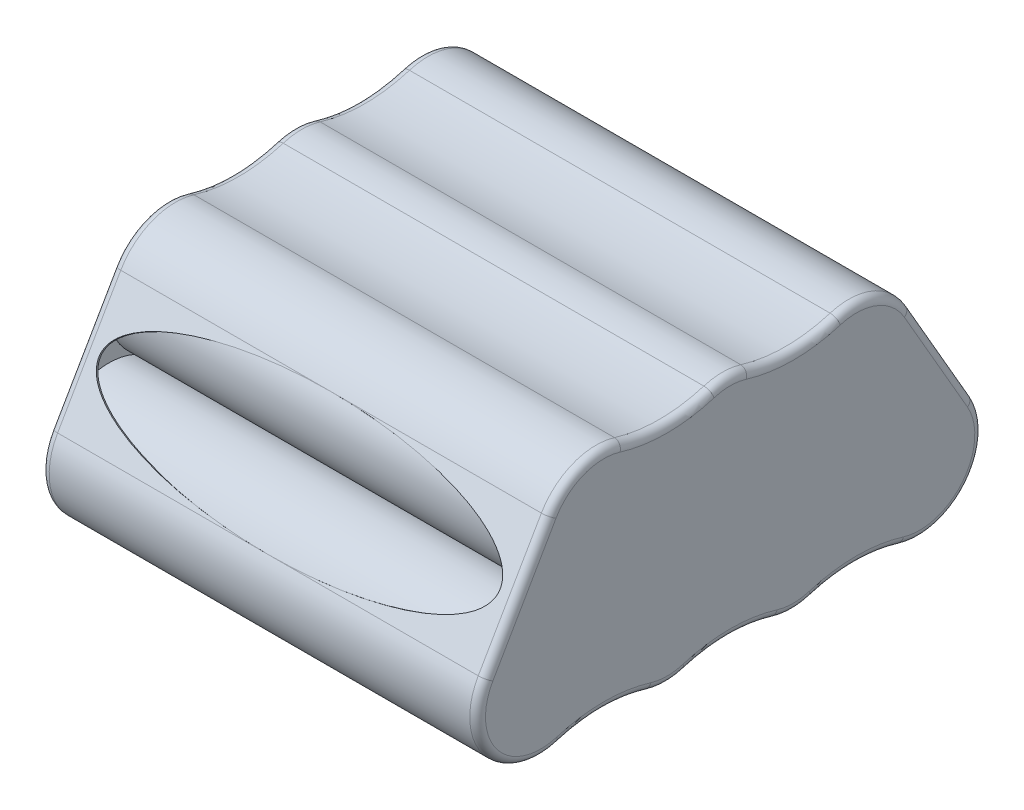
SolidWorks part; units mm, degrees
ref_plane "Front Plane" through (0, 0, 0) normal (0, 0, 1) x (1, 0, 0)
ref_plane "Top Plane" through (0, 0, 0) normal (0, 1, 0) x (1, 0, 0)
ref_plane "Right Plane" through (0, 0, 0) normal (1, 0, 0) x (0, 0, -1)
sketch "Sketch1" plane through (0, 0, 0) normal (1, 0, 0) x (0, 0, -1)
  circle A25 centre (0, 7.2346) radius 7.2346
  circle A26 centre (-14.4693, 7.2346) radius 7.2346
  circle A27 centre (14.4693, 7.2346) radius 7.2346
  circle A28 centre (-7.2346, -5.2961) radius 7.2346
  circle A29 centre (7.2346, -5.2961) radius 7.2346
  circle A30 centre (21.7039, -5.2961) radius 7.2346
  circle A32 centre (-21.7039, -5.2961) radius 7.2346
  circle A33 centre (-7.2346, 30.8876) radius 17.5
  circle A34 centre (7.2346, 30.8876) radius 17.5
  circle A35 centre (38.5706, 12.7957) radius 17.5
  circle A36 centre (14.4693, -28.9491) radius 17.5
  circle A37 centre (0, -28.9491) radius 17.5
  circle A38 centre (-14.4693, -28.9491) radius 17.5
  circle A39 centre (-38.5706, 12.7957) radius 17.5
  point P3 (0, 0)
  point P18 (0, 14.4693)
  point P19 (-7.2346, -12.5307)
  point P36 (0, 0)
  dimension "D1" = 27
  dimension "D2" = 35
extrude "Boss-Extrude2" add sketch "Sketch1" along normal mid plane 50
ref_plane "Plane1" through (0, 11.6913, 20.25) normal (0, 0.5, 0.866) x (1, 0, 0)
sketch "Sketch3" plane through (25, 0, 0) normal (1, 0, 0) x (0, 0, -1)
  line L0 (-20.7346, 10.8519) -> (-27.9693, -1.6788)
  arc A3 (-12.3532, 14.1529) -> (-18.0866, 0.9693) centre (-14.4693, 7.2346) ccw construction
  arc A4 (-18.0866, 0.9693) -> (-19.5878, -12.2144) centre (-21.7039, -5.2961) ccw construction
extrude "Boss-Extrude4" add sketch "Sketch3" against normal blind 0.5
sketch "Sketch4" plane through (-25, 0, 0) normal (-1, 0, 0) x (0, 0, 1)
  line L0 (20.7346, 10.8519) -> (27.9693, -1.6788)
  arc A0 (18.0866, 0.9693) -> (12.3532, 14.1529) centre (14.4693, 7.2346) ccw construction
  arc A1 (19.5878, -12.2144) -> (18.0866, 0.9693) centre (21.7039, -5.2961) ccw construction
  arc M2 (18.0866, 0.9693) -> (12.3532, 14.1529) centre (14.4693, 7.2346) ccw
  arc M13 (19.5878, -12.2144) -> (18.0866, 0.9693) centre (21.7039, -5.2961) ccw
extrude "Boss-Extrude5" add sketch "Sketch4" against normal blind 0.5 contours L0 M2 M13
sketch "Sketch2" plane through (0, 11.6913, 20.25) normal (0, 0.5, 0.866) x (1, 0, 0)
  line L1 (-25, -0.9693) -> (25, -0.9693)
  line L2 (-25, -0.9693) -> (-25, -15.4385)
  line L3 (-25, -15.4385) -> (25, -15.4385)
  line L4 (25, -0.9693) -> (25, -15.4385)
  line L8 (0, -15.4385) -> (0, -0.9693) construction
  ellipse E0 centre (0, -8.2039) end of major axis (-23, -8.2039) minor radius 7.2346
  dimension "D1" = 2
extrude "Boss-Extrude3" add sketch "Sketch2" against normal blind 0.2
mirror "Mirror1" about plane through (0, 0, 0) normal (0, 0, 1) of "Boss-Extrude3", "Boss-Extrude4", "Boss-Extrude5"
fillet "Fillet2" radius 0.9 28 edges at (25, 13.966, -17.1203) (25, 4.5866, -24.3519) (-25, 13.966, -17.1203) (-25, 4.5866, -24.3519) (-25, 13.3876, 7.2346) (-25, 14.4693, 0) (-25, 13.3876, -7.2346) (25, -11.4491, 14.4693) (-25, -9.8001, -27.3655) (-25, -11.4491, -14.4693) (-25, -12.5307, -7.2346) (-25, -11.4491, 0) (-25, -12.5307, 7.2346) (-25, -11.4491, 14.4693) (-25, 13.966, 17.1203) (25, -12.5307, 7.2346) (25, -11.4491, 0) (25, -12.5307, -7.2346) (25, -11.4491, -14.4693) (25, -9.8001, -27.3655) (25, -9.8001, 27.3655) (25, 4.5866, 24.3519) (25, 13.966, 17.1203) (25, 13.3876, -7.2346) (25, 14.4693, 0) (-25, -9.8001, 27.3655) (-25, 4.5866, 24.3519) (25, 13.3876, 7.2346)
fillet "Fillet3" radius 0.5 4 edges at (-24.5, 4.4866, 24.1787) (-24.5, 4.4866, -24.1787) (24.5, 4.4866, -24.1787) (24.5, 4.4866, 24.1787)
